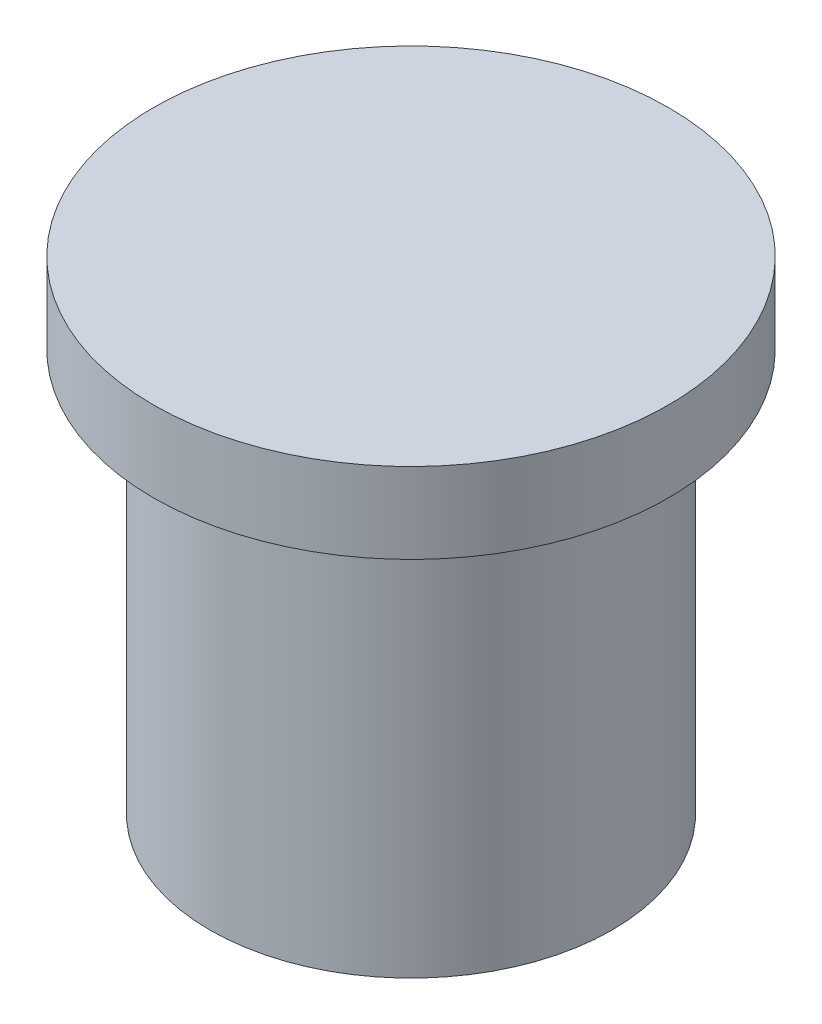
SolidWorks part; units mm, degrees
ref_plane "Спереди" through (0, 0, 0) normal (0, 0, 1) x (1, 0, 0)
ref_plane "Сверху" through (0, 0, 0) normal (0, 1, 0) x (1, 0, 0)
ref_plane "Справа" through (0, 0, 0) normal (1, 0, 0) x (0, 0, -1)
sketch "Эскиз1" plane through (0, 0, 0) normal (0, 1, 0) x (1, 0, 0)
  circle A0 centre (0, 0) radius 2.5
extrude "Бобышка-Вытянуть1" add sketch "Эскиз1" along normal blind 5
sketch "Эскиз2" plane through (0, 5, 0) normal (0, 1, 0) x (1, 0, 0)
  circle A0 centre (0, 0) radius 3.2
extrude "Бобышка-Вытянуть2" add sketch "Эскиз2" along normal blind 1
